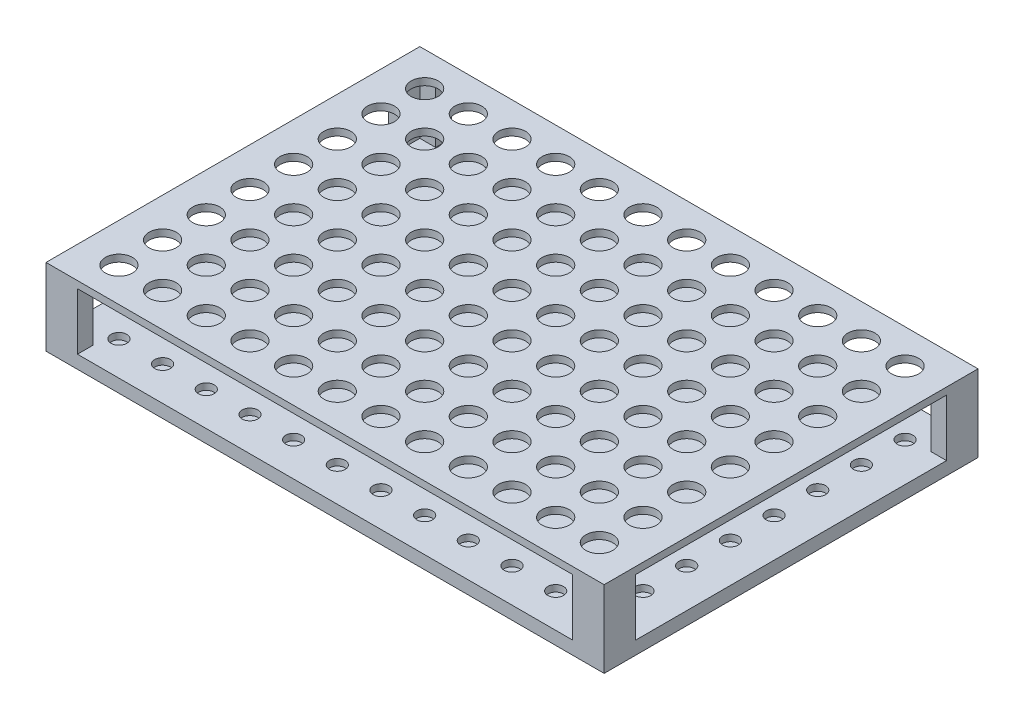
SolidWorks part; units mm, degrees
ref_plane "Front Plane" through (0, 0, 0) normal (0, 0, 1) x (1, 0, 0)
ref_plane "Top Plane" through (0, 0, 0) normal (0, 1, 0) x (1, 0, 0)
ref_plane "Right Plane" through (0, 0, 0) normal (1, 0, 0) x (0, 0, -1)
sketch "Sketch1" plane through (0, 0, 0) normal (0, 1, 0) x (1, 0, 0)
  line L1 (63.9, -42.8) -> (-63.9, -42.8)
  line L2 (63.9, -42.8) -> (63.9, 42.8)
  line L3 (63.9, 42.8) -> (-63.9, 42.8)
  line L4 (-63.9, -42.8) -> (-63.9, 42.8)
  line L5 (63.9, -42.8) -> (-63.9, 42.8) construction
  line L6 (63.9, 42.8) -> (-63.9, -42.8) construction
  point P0 (0, 0)
  dimension "D1" = 127.8
  dimension "D2" = 85.6
extrude "Boss-Extrude1" add sketch "Sketch1" along normal blind 3
sketch "Sketch2" plane through (0, 3, 0) normal (0, 1, 0) x (1, 0, 0)
  line L0 (-63.9, 42.8) -> (-56.7, 42.8)
  line L5 (63.9, 42.8) -> (-63.9, 42.8) construction
  line L6 (-56.7, 42.8) -> (-56.7, 39.2)
  line L7 (-56.7, 39.2) -> (-60.3, 39.2)
  line L8 (-60.3, 39.2) -> (-60.3, 35.6)
  line L9 (-60.3, 35.6) -> (-63.9, 35.6)
  line L10 (-63.9, 42.8) -> (-63.9, -42.8) construction
  line L11 (-63.9, 35.6) -> (-63.9, 42.8)
  line L12 (0, 42.8) -> (0, -42.8) construction
  line L13 (-63.9, -42.8) -> (63.9, -42.8) construction
  line L14 (-63.9, 0) -> (63.9, 0) construction
  line L15 (63.9, -42.8) -> (63.9, 42.8) construction
  line L16 (63.9, 35.6) -> (63.9, 42.8)
  line L17 (60.3, 35.6) -> (63.9, 35.6)
  line L18 (60.3, 39.2) -> (60.3, 35.6)
  line L19 (56.7, 39.2) -> (60.3, 39.2)
  line L20 (56.7, 42.8) -> (56.7, 39.2)
  line L21 (63.9, 42.8) -> (56.7, 42.8)
  line L22 (63.9, -42.8) -> (56.7, -42.8)
  line L23 (56.7, -42.8) -> (56.7, -39.2)
  line L24 (56.7, -39.2) -> (60.3, -39.2)
  line L25 (60.3, -39.2) -> (60.3, -35.6)
  line L26 (60.3, -35.6) -> (63.9, -35.6)
  line L27 (63.9, -35.6) -> (63.9, -42.8)
  line L28 (-63.9, -35.6) -> (-63.9, -42.8)
  line L29 (-60.3, -35.6) -> (-63.9, -35.6)
  line L30 (-60.3, -39.2) -> (-60.3, -35.6)
  line L31 (-56.7, -39.2) -> (-60.3, -39.2)
  line L32 (-56.7, -42.8) -> (-56.7, -39.2)
  line L33 (-63.9, -42.8) -> (-56.7, -42.8)
  dimension "D1" = 7.2
  dimension "D2" = 7.2
  dimension "D3" = 3.6
  dimension "D4" = 3.6
extrude "Boss-Extrude2" add sketch "Sketch2" along normal blind 13
ref_plane "Plane2" through (0, 16, 0) normal (0, 1, 0) x (1, 0, 0)
sketch "Sketch3" plane through (0, 16, 0) normal (0, 1, 0) x (1, 0, 0)
  line L1 (-63.9, 42.8) -> (63.9, 42.8)
  line L2 (-63.9, 42.8) -> (-63.9, -42.8)
  line L3 (-63.9, -42.8) -> (63.9, -42.8)
  line L4 (63.9, 42.8) -> (63.9, -42.8)
extrude "Boss-Extrude3" add sketch "Sketch3" along normal blind 1.6
ref_plane "Plane3" through (0, 17.6, 0) normal (0, 1, 0) x (1, 0, 0)
sketch "Sketch6" plane through (0, 17.6, 0) normal (0, 1, 0) x (1, 0, 0)
  line L1 (-63.9, 42.8) -> (-63.9, -42.8) construction
  line L6 (63.9, 42.8) -> (-63.9, 42.8) construction
  line L8 (0, 42.8) -> (0, -42.8) construction
  line L9 (-63.9, -42.8) -> (63.9, -42.8) construction
  circle A0 centre (-55, 35) radius 3.1
  circle A1 centre (-45, 35) radius 3.1
  circle A2 centre (-35, 35) radius 3.1
  circle A3 centre (-25, 35) radius 3.1
  circle A4 centre (-15, 35) radius 3.1
  circle A5 centre (-5, 35) radius 3.1
  circle A6 centre (5, 35) radius 3.1
  circle A7 centre (15, 35) radius 3.1
  circle A8 centre (25, 35) radius 3.1
  circle A9 centre (35, 35) radius 3.1
  circle A10 centre (45, 35) radius 3.1
  circle A11 centre (55, 35) radius 3.1
  circle A19 centre (-55, 25) radius 3.1
  circle A20 centre (-55, 15) radius 3.1
  circle A21 centre (-55, 5) radius 3.1
  circle A22 centre (-55, -5) radius 3.1
  circle A23 centre (-55, -15) radius 3.1
  circle A24 centre (-55, -25) radius 3.1
  circle A25 centre (-55, -35) radius 3.1
  circle A26 centre (-45, 25) radius 3.1
  circle A27 centre (-45, 15) radius 3.1
  circle A28 centre (-45, 5) radius 3.1
  circle A29 centre (-45, -5) radius 3.1
  circle A30 centre (-45, -15) radius 3.1
  circle A31 centre (-45, -25) radius 3.1
  circle A32 centre (-45, -35) radius 3.1
  circle A33 centre (-35, 25) radius 3.1
  circle A34 centre (-35, 15) radius 3.1
  circle A35 centre (-35, 5) radius 3.1
  circle A36 centre (-35, -5) radius 3.1
  circle A37 centre (-35, -15) radius 3.1
  circle A38 centre (-35, -25) radius 3.1
  circle A39 centre (-35, -35) radius 3.1
  circle A40 centre (-25, 25) radius 3.1
  circle A41 centre (-25, 15) radius 3.1
  circle A42 centre (-25, 5) radius 3.1
  circle A43 centre (-25, -5) radius 3.1
  circle A44 centre (-25, -15) radius 3.1
  circle A45 centre (-25, -25) radius 3.1
  circle A46 centre (-25, -35) radius 3.1
  circle A47 centre (-15, 25) radius 3.1
  circle A48 centre (-15, 15) radius 3.1
  circle A49 centre (-15, 5) radius 3.1
  circle A50 centre (-15, -5) radius 3.1
  circle A51 centre (-15, -15) radius 3.1
  circle A52 centre (-15, -25) radius 3.1
  circle A53 centre (-15, -35) radius 3.1
  circle A54 centre (-5, 25) radius 3.1
  circle A55 centre (-5, 15) radius 3.1
  circle A56 centre (-5, 5) radius 3.1
  circle A57 centre (-5, -5) radius 3.1
  circle A58 centre (-5, -15) radius 3.1
  circle A59 centre (-5, -25) radius 3.1
  circle A60 centre (-5, -35) radius 3.1
  circle A61 centre (5, 25) radius 3.1
  circle A62 centre (5, 15) radius 3.1
  circle A63 centre (5, 5) radius 3.1
  circle A64 centre (5, -5) radius 3.1
  circle A65 centre (5, -15) radius 3.1
  circle A66 centre (5, -25) radius 3.1
  circle A67 centre (5, -35) radius 3.1
  circle A68 centre (15, 25) radius 3.1
  circle A69 centre (15, 15) radius 3.1
  circle A70 centre (15, 5) radius 3.1
  circle A71 centre (15, -5) radius 3.1
  circle A72 centre (15, -15) radius 3.1
  circle A73 centre (15, -25) radius 3.1
  circle A74 centre (15, -35) radius 3.1
  circle A75 centre (25, 25) radius 3.1
  circle A76 centre (25, 15) radius 3.1
  circle A77 centre (25, 5) radius 3.1
  circle A78 centre (25, -5) radius 3.1
  circle A79 centre (25, -15) radius 3.1
  circle A80 centre (25, -25) radius 3.1
  circle A81 centre (25, -35) radius 3.1
  circle A82 centre (35, 25) radius 3.1
  circle A83 centre (35, 15) radius 3.1
  circle A84 centre (35, 5) radius 3.1
  circle A85 centre (35, -5) radius 3.1
  circle A86 centre (35, -15) radius 3.1
  circle A87 centre (35, -25) radius 3.1
  circle A88 centre (35, -35) radius 3.1
  circle A89 centre (45, 25) radius 3.1
  circle A90 centre (45, 15) radius 3.1
  circle A91 centre (45, 5) radius 3.1
  circle A92 centre (45, -5) radius 3.1
  circle A93 centre (45, -15) radius 3.1
  circle A94 centre (45, -25) radius 3.1
  circle A95 centre (45, -35) radius 3.1
  circle A96 centre (55, 25) radius 3.1
  circle A97 centre (55, 15) radius 3.1
  circle A98 centre (55, 5) radius 3.1
  circle A99 centre (55, -5) radius 3.1
  circle A100 centre (55, -15) radius 3.1
  circle A101 centre (55, -25) radius 3.1
  circle A102 centre (55, -35) radius 3.1
  dimension "D5" = 12
  dimension "D1" = 6.2
  dimension "D6" = 8.9
  dimension "D8" = 7.8
extrude "Cut-Extrude1" cut sketch "Sketch6" against normal blind 1.6
ref_plane "Plane4" through (0, 3, 0) normal (0, 1, 0) x (1, 0, 0)
sketch "Sketch8" plane through (0, 3, 0) normal (0, 1, 0) x (1, 0, 0)
  line L0 (-63.9, 35.6) -> (-63.9, -35.6) construction
  line L1 (56.7, 42.8) -> (-56.7, 42.8) construction
  circle A0 centre (-55, 35) radius 1.8
  circle A1 centre (-45, 35) radius 1.8
  circle A2 centre (-35, 35) radius 1.8
  circle A3 centre (-25, 35) radius 1.8
  circle A4 centre (-15, 35) radius 1.8
  circle A5 centre (-5, 35) radius 1.8
  circle A6 centre (5, 35) radius 1.8
  circle A7 centre (15, 35) radius 1.8
  circle A8 centre (25, 35) radius 1.8
  circle A9 centre (35, 35) radius 1.8
  circle A10 centre (45, 35) radius 1.8
  circle A11 centre (55, 35) radius 1.8
  circle A12 centre (-55, 25) radius 1.8
  circle A13 centre (-55, 15) radius 1.8
  circle A14 centre (-55, 5) radius 1.8
  circle A15 centre (-55, -5) radius 1.8
  circle A16 centre (-55, -15) radius 1.8
  circle A17 centre (-55, -25) radius 1.8
  circle A18 centre (-55, -35) radius 1.8
  circle A19 centre (-45, 25) radius 1.8
  circle A20 centre (-45, 15) radius 1.8
  circle A21 centre (-45, 5) radius 1.8
  circle A22 centre (-45, -5) radius 1.8
  circle A23 centre (-45, -15) radius 1.8
  circle A24 centre (-45, -25) radius 1.8
  circle A25 centre (-45, -35) radius 1.8
  circle A26 centre (-35, 25) radius 1.8
  circle A27 centre (-35, 15) radius 1.8
  circle A28 centre (-35, 5) radius 1.8
  circle A29 centre (-35, -5) radius 1.8
  circle A30 centre (-35, -15) radius 1.8
  circle A31 centre (-35, -25) radius 1.8
  circle A32 centre (-35, -35) radius 1.8
  circle A33 centre (-25, 25) radius 1.8
  circle A34 centre (-25, 15) radius 1.8
  circle A35 centre (-25, 5) radius 1.8
  circle A36 centre (-25, -5) radius 1.8
  circle A37 centre (-25, -15) radius 1.8
  circle A38 centre (-25, -25) radius 1.8
  circle A39 centre (-25, -35) radius 1.8
  circle A40 centre (-15, 25) radius 1.8
  circle A41 centre (-15, 15) radius 1.8
  circle A42 centre (-15, 5) radius 1.8
  circle A43 centre (-15, -5) radius 1.8
  circle A44 centre (-15, -15) radius 1.8
  circle A45 centre (-15, -25) radius 1.8
  circle A46 centre (-15, -35) radius 1.8
  circle A47 centre (-5, 25) radius 1.8
  circle A48 centre (-5, 15) radius 1.8
  circle A49 centre (-5, 5) radius 1.8
  circle A50 centre (-5, -5) radius 1.8
  circle A51 centre (-5, -15) radius 1.8
  circle A52 centre (-5, -25) radius 1.8
  circle A53 centre (-5, -35) radius 1.8
  circle A54 centre (5, 25) radius 1.8
  circle A55 centre (5, 15) radius 1.8
  circle A56 centre (5, 5) radius 1.8
  circle A57 centre (5, -5) radius 1.8
  circle A58 centre (5, -15) radius 1.8
  circle A59 centre (5, -25) radius 1.8
  circle A60 centre (5, -35) radius 1.8
  circle A61 centre (15, 25) radius 1.8
  circle A62 centre (15, 15) radius 1.8
  circle A63 centre (15, 5) radius 1.8
  circle A64 centre (15, -5) radius 1.8
  circle A65 centre (15, -15) radius 1.8
  circle A66 centre (15, -25) radius 1.8
  circle A67 centre (15, -35) radius 1.8
  circle A68 centre (25, 25) radius 1.8
  circle A69 centre (25, 15) radius 1.8
  circle A70 centre (25, 5) radius 1.8
  circle A71 centre (25, -5) radius 1.8
  circle A72 centre (25, -15) radius 1.8
  circle A73 centre (25, -25) radius 1.8
  circle A74 centre (25, -35) radius 1.8
  circle A75 centre (35, 25) radius 1.8
  circle A76 centre (35, 15) radius 1.8
  circle A77 centre (35, 5) radius 1.8
  circle A78 centre (35, -5) radius 1.8
  circle A79 centre (35, -15) radius 1.8
  circle A80 centre (35, -25) radius 1.8
  circle A81 centre (35, -35) radius 1.8
  circle A82 centre (45, 25) radius 1.8
  circle A83 centre (45, 15) radius 1.8
  circle A84 centre (45, 5) radius 1.8
  circle A85 centre (45, -5) radius 1.8
  circle A86 centre (45, -15) radius 1.8
  circle A87 centre (45, -25) radius 1.8
  circle A88 centre (45, -35) radius 1.8
  circle A89 centre (55, 25) radius 1.8
  circle A90 centre (55, 15) radius 1.8
  circle A91 centre (55, 5) radius 1.8
  circle A92 centre (55, -5) radius 1.8
  circle A93 centre (55, -15) radius 1.8
  circle A94 centre (55, -25) radius 1.8
  circle A95 centre (55, -35) radius 1.8
  dimension "D1" = 8.9
  dimension "D2" = 7.8
  dimension "D3" = 12
extrude "Cut-Extrude2" cut sketch "Sketch8" against normal blind 1.5
